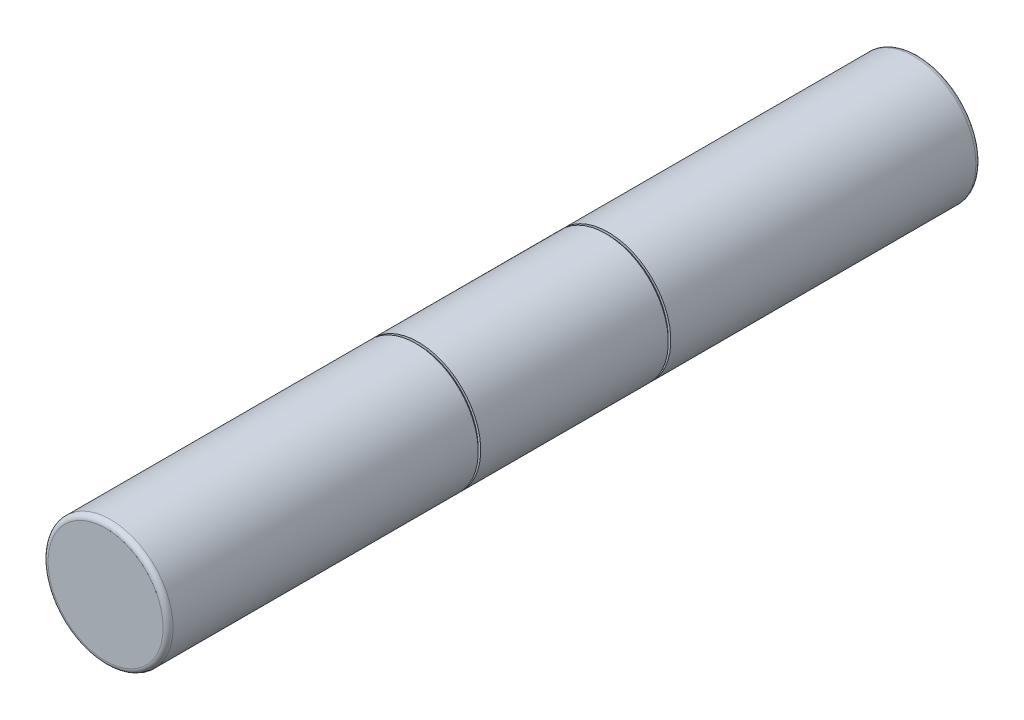
SolidWorks part; units mm, degrees
ref_plane "Front Plane" through (0, 0, 0) normal (0, 0, 1) x (1, 0, 0)
ref_plane "Top Plane" through (0, 0, 0) normal (0, 1, 0) x (1, 0, 0)
ref_plane "Right Plane" through (0, 0, 0) normal (1, 0, 0) x (0, 0, -1)
sketch "Sketch1" plane through (0, 0, 0) normal (0, 0, 1) x (1, 0, 0)
  circle A0 centre (0, 0) radius 3.175
  dimension "D1" = 6.35
extrude "Boss-Extrude1" add sketch "Sketch1" along normal mid plane 41.275
ref_plane "Plane3" through (0, 3.175, 0) normal (0, 1, 0) x (1, 0, 0)
sketch "Sketch5" plane through (0, 3.175, 0) normal (0, 1, 0) x (1, 0, 0)
  line L0 (0, -4.7625) -> (0, 4.7625)
  line L2 (0, -3.4925) -> (0, 3.4925) construction
  line L3 (-3.175, 4.7625) -> (3.175, 4.7625)
  line L4 (3.175, -20.6375) -> (3.175, 20.6375) construction
  line L5 (-3.175, 4.7625) -> (-3.175, 4.8895)
  line L6 (-3.175, 20.6375) -> (-3.175, -20.6375) construction
  line L7 (-3.175, 4.8895) -> (3.175, 4.8895)
  line L8 (3.175, 4.8895) -> (3.175, 4.7625)
  line L9 (-5.2047, 0) -> (5.2047, 0) construction
  line L10 (-3.175, -4.7625) -> (-3.175, -4.8895)
  line L11 (3.175, -4.8895) -> (3.175, -4.7625)
  line L12 (-3.175, -4.8895) -> (3.175, -4.8895)
  line L13 (-3.175, -4.7625) -> (3.175, -4.7625)
  point P4 (0, 0)
  point P12 (0, 4.7625)
  point P19 (0, 0)
  dimension "D1" = 9.525
  dimension "D2" = 0.127
curve "Curve1"
ref_plane "Plane4" through (0, 0, -4.8895) normal (0, 0, -1) x (-1, 0, 0)
sketch "Sketch6" plane through (0, 0, -4.8895) normal (0, 0, -1) x (-1, 0, 0)
  circle A0 centre (0, 0) radius 3.175
  circle A1 centre (0, 0) radius 3.048
  dimension "D1" = 6.35
  dimension "D2" = 6.096
extrude "Cut-Extrude1" cut sketch "Sketch6" against normal blind 0.127
ref_plane "Plane5" through (0, 0, 4.7625) normal (0, 0, -1) x (-1, 0, 0)
sketch "Sketch7" plane through (0, 0, 4.7625) normal (0, 0, -1) x (-1, 0, 0)
  circle A0 centre (0, 0) radius 3.175
  circle A1 centre (0, 0) radius 3.048
  dimension "D1" = 6.35
  dimension "D2" = 6.096
extrude "Cut-Extrude2" cut sketch "Sketch7" against normal blind 0.127
fillet "Fillet1" radius 0.254 2 edges at (3.175, 0, 20.6375) (3.175, 0, -20.6375)
